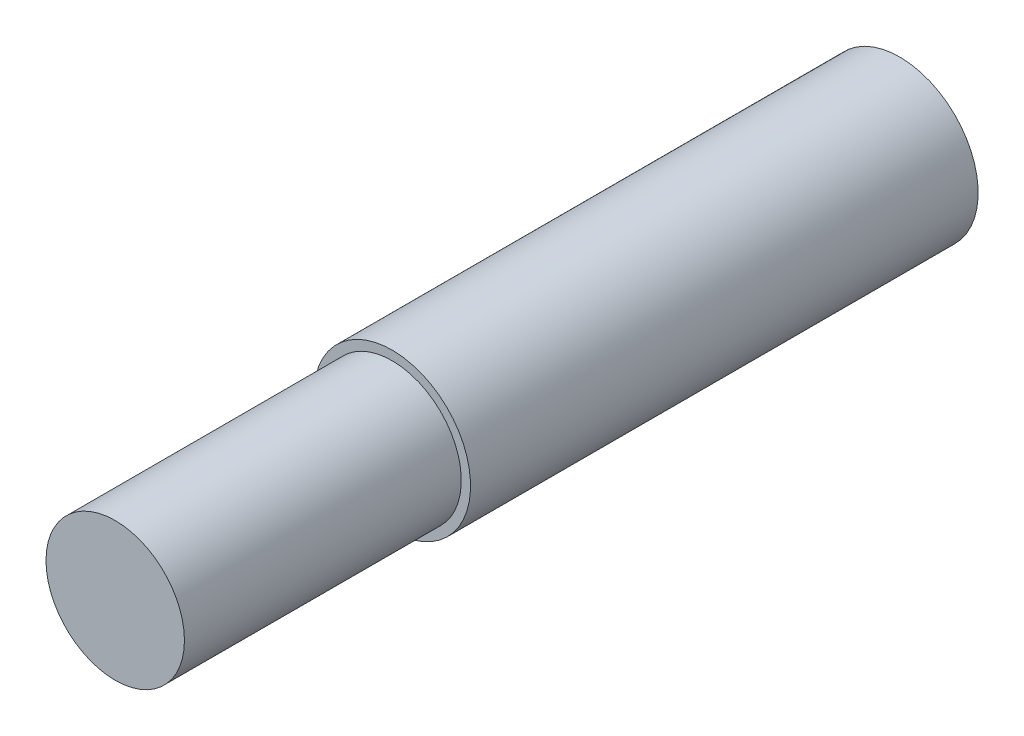
SolidWorks part; units mm, degrees
ref_plane "Front Plane" through (0, 0, 0) normal (0, 0, 1) x (1, 0, 0)
ref_plane "Top Plane" through (0, 0, 0) normal (0, 1, 0) x (1, 0, 0)
ref_plane "Right Plane" through (0, 0, 0) normal (1, 0, 0) x (0, 0, -1)
sketch "Sketch1" plane through (0, 0, 0) normal (0, 0, 1) x (1, 0, 0)
  circle A0 centre (0, 0) radius 7.5
  dimension "D1" = 15
extrude "Boss-Extrude1" add sketch "Sketch1" along normal blind 30
sketch "Sketch2" plane through (0, 0, 0) normal (0, 0, -1) x (-1, 0, 0)
  circle A0 centre (0, 0) radius 8.5
  circle A1 centre (0, 0) radius 6
  circle A2 centre (0, 0) radius 7.5 construction
  dimension "D1" = 1
  dimension "D2" = 12
extrude "Boss-Extrude2" add sketch "Sketch2" along normal blind 55
sketch "Sketch3" plane through (0, 0, 0) normal (0, 0, -1) x (-1, 0, 0)
  circle A0 centre (0, 0) radius 6 construction
  circle A1 centre (0, 0) radius 6
extrude "Boss-Extrude3" add sketch "Sketch3" along normal blind 3
